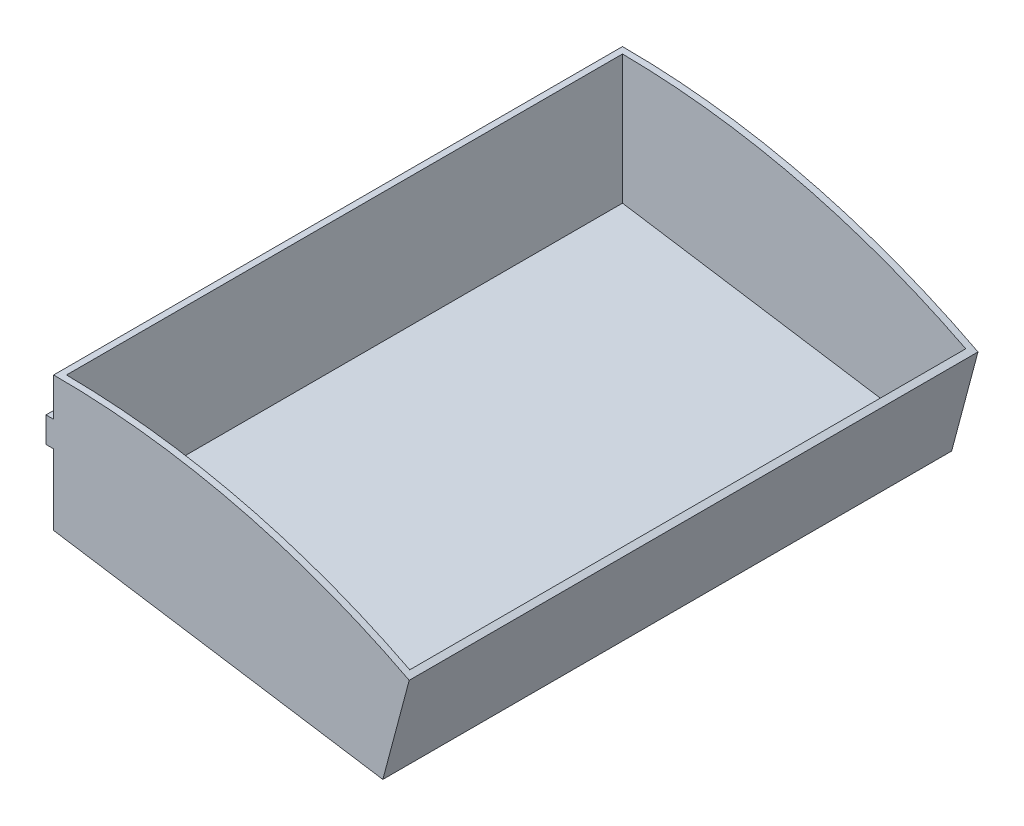
SolidWorks part; units mm, degrees
ref_plane "Front Plane" through (0, 0, 0) normal (0, 0, 1) x (1, 0, 0)
ref_plane "Top Plane" through (0, 0, 0) normal (0, 1, 0) x (1, 0, 0)
ref_plane "Right Plane" through (0, 0, 0) normal (1, 0, 0) x (0, 0, -1)
sketch "Sketch1" plane through (0, 0, 0) normal (0, 0, 1) x (1, 0, 0)
  line L0 (0, 0) -> (0, 133.572)
  line L1 (352.425, 47.6067) -> (326.3034, -50.578)
  line L2 (326.3034, -50.578) -> (0, 0)
  arc A0 (0, 133.572) -> (352.425, 47.6067) centre (0, -631.8143) cw
  dimension "D1" = 184.15
  dimension "D2" = 352.425
  dimension "D3" = 330.2
  dimension "D4" = 101.6
extrude "Boss-Extrude1" add sketch "Sketch1" along normal blind 563.88
shell "Shell1" thickness 6.35
sketch "Sketch2" plane through (0, 0, 0) normal (-1, 0, 0) x (0, 0, 1)
  line L7 (0, 133.572) -> (0, 0) construction
  line L8 (0, 95.472) -> (563.88, 95.472)
  line L9 (0, 95.472) -> (0, 70.072)
  line L10 (0, 70.072) -> (563.88, 70.072)
  line L11 (563.88, 95.472) -> (563.88, 70.072)
  line L12 (563.88, 133.572) -> (563.88, 0) construction
  line L13 (563.88, 133.572) -> (0, 133.572) construction
  dimension "D1" = 38.1
  dimension "D2" = 25.4
extrude "Boss-Extrude2" add sketch "Sketch2" along normal blind 7.62
